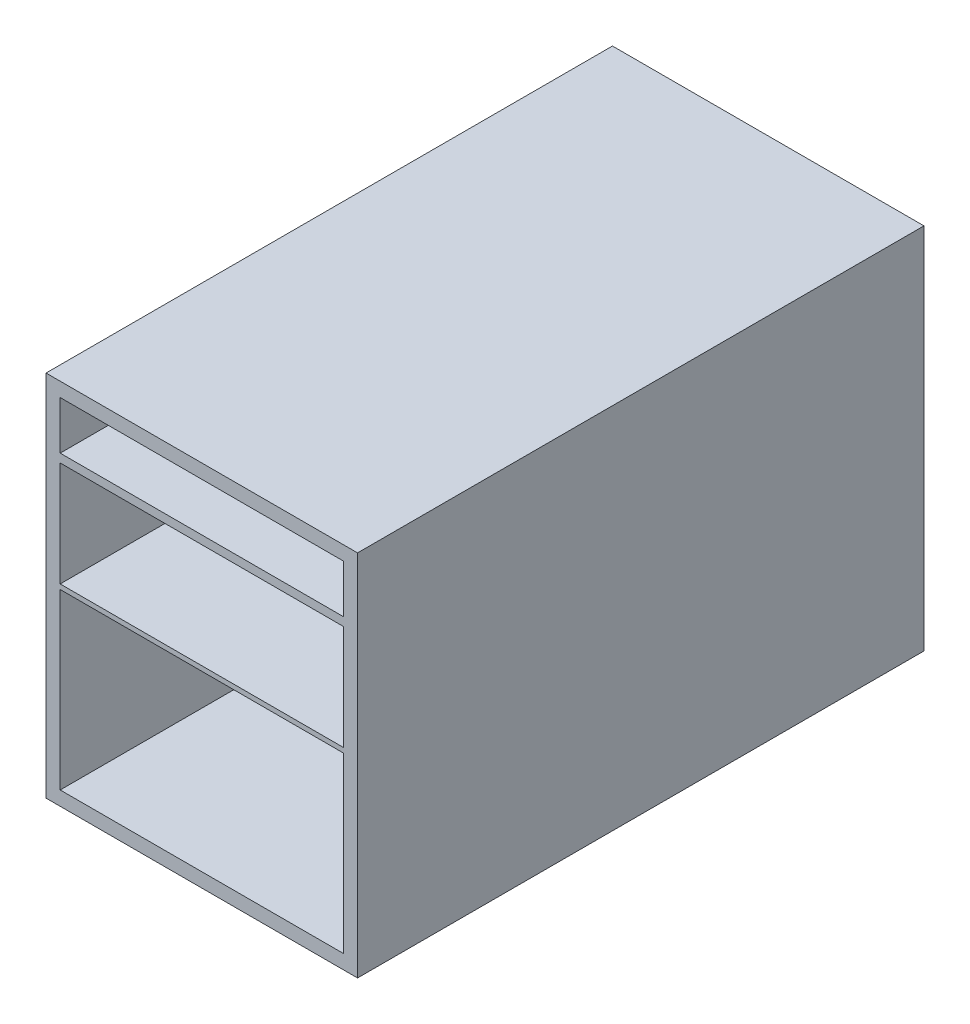
SolidWorks part; units mm, degrees
ref_plane "Front Plane" through (0, 0, 0) normal (0, 0, 1) x (1, 0, 0)
ref_plane "Top Plane" through (0, 0, 0) normal (0, 1, 0) x (1, 0, 0)
ref_plane "Right Plane" through (0, 0, 0) normal (1, 0, 0) x (0, 0, -1)
sketch "Sketch1" plane through (0, 0, 0) normal (0, 0, 1) x (1, 0, 0)
  line L1 (55, -65) -> (-55, -65)
  line L2 (55, -65) -> (55, 65)
  line L3 (55, 65) -> (-55, 65)
  line L4 (-55, -65) -> (-55, 65)
  line L5 (55, -65) -> (-55, 65) construction
  line L6 (55, 65) -> (-55, -65) construction
  point P0 (0, 0)
  dimension "D1" = 130
  dimension "D2" = 110
extrude "Boss-Extrude1" add sketch "Sketch1" along normal blind 200
shell "Shell1" thickness 5
sketch "Sketch2" plane through (0, 0, 0) normal (0, 0, -1) x (-1, 0, 0)
  line L0 (55, -65) -> (-55, -65) construction
  line L1 (55, 3) -> (-55, 3)
  line L2 (55, 3) -> (55, 1.3)
  line L3 (55, 1.3) -> (-55, 1.3)
  line L4 (-55, 3) -> (-55, 1.3)
  line L5 (55, 3) -> (-55, 1.3) construction
  line L6 (55, 1.3) -> (-55, 3) construction
  line L13 (-55, -65) -> (-55, 65) construction
  line L14 (55, 65) -> (55, -65) construction
  point P0 (0, 2.15)
  point P7 (0, 0)
  point P10 (-18.1901, 2.15)
  point P11 (0, 0)
  point P12 (-18.1901, 2.15)
  dimension "D1" = 68
extrude "Boss-Extrude2" add sketch "Sketch2" against normal up to surface (200 mm away) up to face at (0, 0, 200)
ref_plane "Plane1" through (55, -65, 0) normal (1, 0, 0) x (0, 0, -1)
ref_plane "Plane2" through (50, 3, 5) normal (-1, 0, 0) x (0, 0, 1)
sketch "Sketch5" plane through (0, 0, 0) normal (0, 0, -1) x (-1, 0, 0)
  line L0 (-55, -65) -> (-55, 65) construction
  line L1 (55, 40) -> (-55, 40)
  line L2 (55, 40) -> (55, 43)
  line L3 (55, 43) -> (-55, 43)
  line L4 (-55, 40) -> (-55, 43)
  line L5 (55, 40) -> (-55, 43) construction
  line L6 (55, 43) -> (-55, 40) construction
  line L7 (55, -65) -> (-55, -65) construction
  line L8 (55, 65) -> (55, -65) construction
  point P0 (0, 41.5)
  dimension "D1" = 105
  dimension "D2" = 3
extrude "Boss-Extrude3" add sketch "Sketch5" against normal up to surface (200 mm away) up to face at (0, -29.35, 200)
